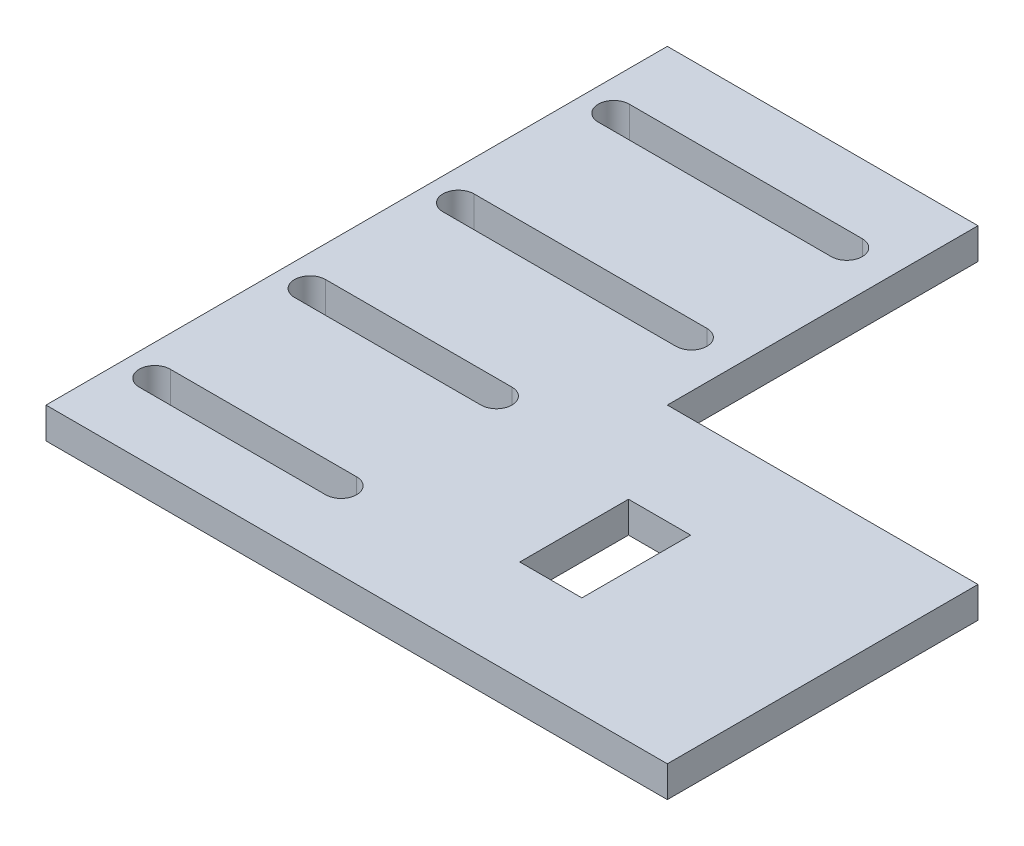
SolidWorks part; units mm, degrees
ref_plane "Front Plane" through (0, 0, 0) normal (0, 0, 1) x (1, 0, 0)
ref_plane "Top Plane" through (0, 0, 0) normal (0, 1, 0) x (1, 0, 0)
ref_plane "Right Plane" through (0, 0, 0) normal (1, 0, 0) x (0, 0, -1)
sketch "Sketch2" plane through (0, 0, 0) normal (0, 1, 0) x (1, 0, 0)
  line L1 (-50, 25) -> (50, 25)
  line L2 (-50, 25) -> (-50, -25)
  line L3 (-50, -25) -> (50, -25)
  line L4 (50, 25) -> (50, -25)
  line L5 (-50, 25) -> (50, -25) construction
  line L6 (-50, -25) -> (50, 25) construction
  point P0 (0, 0)
  dimension "D1" = 50
  dimension "D2" = 100
extrude "Boss-Extrude1" add sketch "Sketch2" along normal blind 5
sketch "Sketch3" plane through (0, 5, 0) normal (0, 1, 0) x (1, 0, 0)
  line L0 (0, 0) -> (15, 0) construction
  line L2 (10, 8.75) -> (20, 8.75)
  line L3 (10, 8.75) -> (10, -8.75)
  line L4 (10, -8.75) -> (20, -8.75)
  line L5 (20, 8.75) -> (20, -8.75)
  line L6 (10, 8.75) -> (20, -8.75) construction
  line L7 (10, -8.75) -> (20, 8.75) construction
  dimension "D1" = 15
  dimension "D2" = 10
  dimension "D3" = 17.5
extrude "Cut-Extrude1" cut sketch "Sketch3" against normal blind 7.5
sketch "Sketch4" plane through (0, 5, 0) normal (0, 1, 0) x (1, 0, 0)
  line L0 (-45, 12.5) -> (-15, 12.5) construction
  line L1 (-45, 15) -> (-15, 15)
  line L2 (-45, 10) -> (-15, 10)
  line L3 (-50, 25) -> (-50, -25) construction
  line L4 (50, 25) -> (-50, 25) construction
  line L5 (-45, -15) -> (-15, -15)
  line L6 (-45, -10) -> (-15, -10)
  line L7 (-45, -12.5) -> (-15, -12.5) construction
  arc A0 (-45, 15) -> (-45, 10) centre (-45, 12.5) ccw
  arc A1 (-15, 10) -> (-15, 15) centre (-15, 12.5) ccw
  arc A2 (-45, -10) -> (-45, -15) centre (-45, -12.5) ccw
  arc A3 (-15, -15) -> (-15, -10) centre (-15, -12.5) ccw
  point P2 (-30, 12.5)
  point P14 (-30, -12.5)
  dimension "D1" = 5
  dimension "D2" = 5
  dimension "D3" = 10
  dimension "D5" = 30
  dimension "D4" = 2
extrude "Cut-Extrude2" cut sketch "Sketch4" against normal blind 7.5
sketch "Sketch5" plane through (0, 5, 0) normal (0, 1, 0) x (1, 0, 0)
  line L0 (-50, 25) -> (-50, 75)
  line L1 (-50, 75) -> (0, 75)
  line L2 (0, 75) -> (0, 25)
  line L3 (50, 25) -> (-50, 25) construction
  line L4 (0, 25) -> (-50, 25)
  dimension "D1" = 50
extrude "Boss-Extrude2" add sketch "Sketch5" against normal up to surface (5 mm away) up to face at (-30, 0, -12.5)
sketch "Sketch6" plane through (0, 5, 0) normal (0, 1, 0) x (1, 0, 0)
  line L0 (-45, 36.3803) -> (-7.5, 36.3803) construction
  line L1 (-45, 38.8803) -> (-7.5, 38.8803)
  line L2 (-45, 33.8803) -> (-7.5, 33.8803)
  line L3 (-50, 75) -> (-50, -25) construction
  line L4 (0, 25) -> (0, 75) construction
  arc A0 (-45, 38.8803) -> (-45, 33.8803) centre (-45, 36.3803) ccw
  arc A1 (-7.5, 33.8803) -> (-7.5, 38.8803) centre (-7.5, 36.3803) ccw
  point P2 (-26.25, 36.3803)
  point P9 (-5, 36.3803)
  dimension "D2" = 5
  dimension "D1" = 5
  dimension "D3" = 5
extrude "Cut-Extrude3" cut sketch "Sketch6" against normal blind 10
pattern_linear "LPattern1" count 2 spacing 25 along (0, 0, -1) of "Cut-Extrude3"
